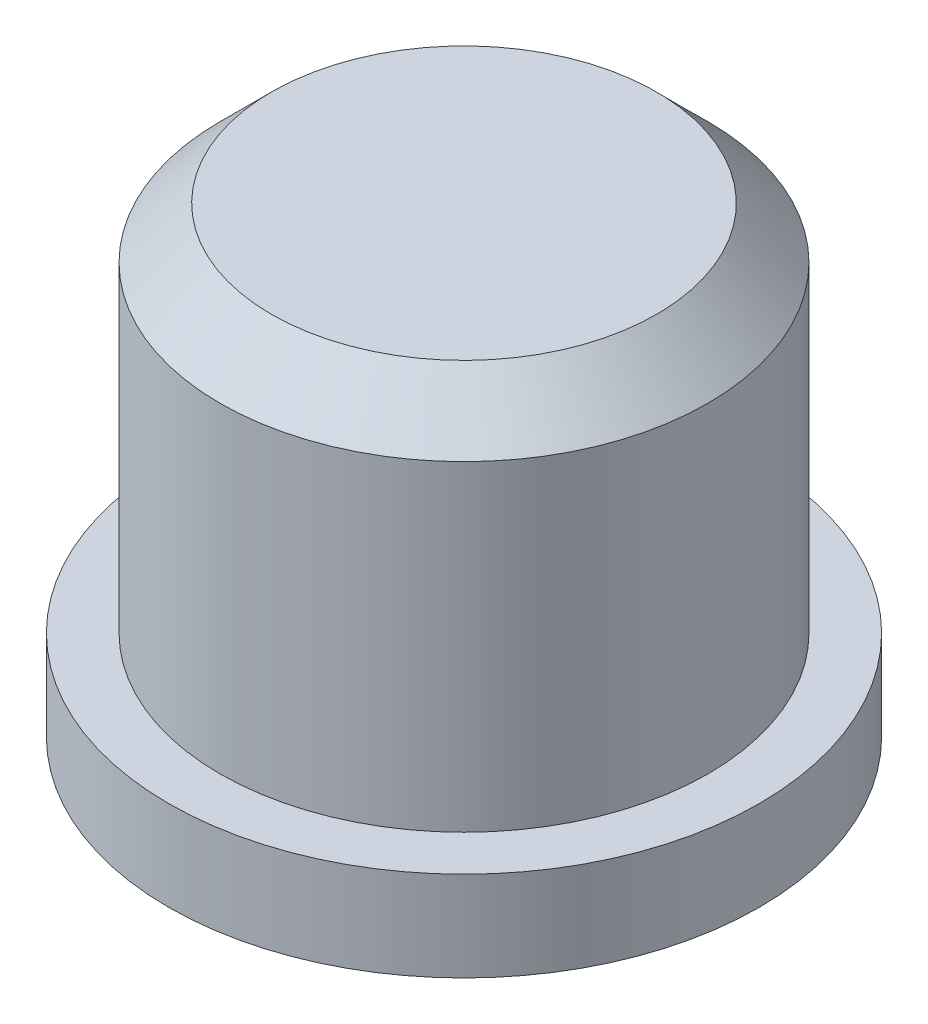
SolidWorks part; units mm, degrees
ref_plane "Front Plane" through (0, 0, 0) normal (0, 0, 1) x (1, 0, 0)
ref_plane "Top Plane" through (0, 0, 0) normal (0, 1, 0) x (1, 0, 0)
ref_plane "Right Plane" through (0, 0, 0) normal (1, 0, 0) x (0, 0, -1)
sketch "Sketch1" plane through (0, 0, 0) normal (0, 1, 0) x (1, 0, 0)
  circle A0 centre (0, 0) radius 4.75
extrude "Boss-Extrude1" add sketch "Sketch1" along normal blind 9
sketch "Sketch2" plane through (0, 0, 0) normal (0, -1, 0) x (1, 0, 0)
  circle A0 centre (0, 0) radius 5.75
extrude "Boss-Extrude2" add sketch "Sketch2" against normal blind 1.75
chamfer "Chamfer1" distance 1 angle 45 1 edges at (0, 9, 4.75)
